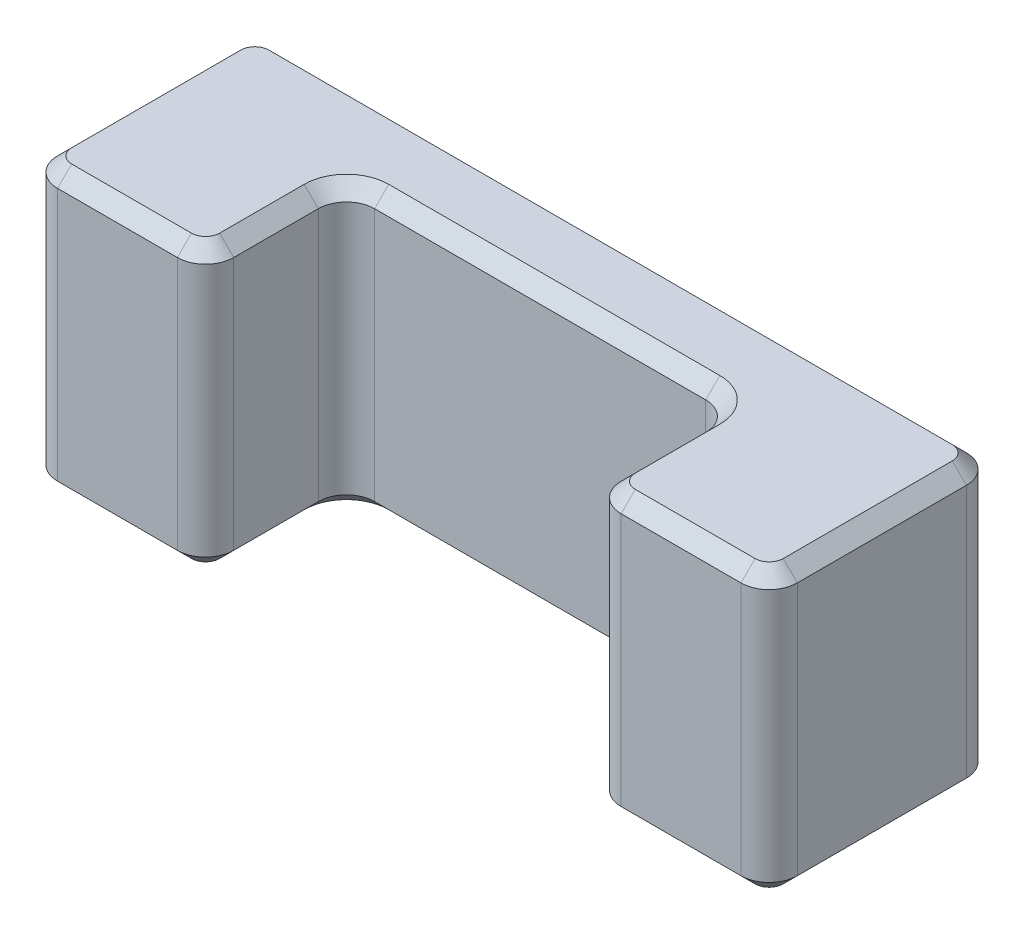
SolidWorks part; units mm, degrees
ref_plane "Front Plane" through (0, 0, 0) normal (0, 0, 1) x (1, 0, 0)
ref_plane "Top Plane" through (0, 0, 0) normal (0, 1, 0) x (1, 0, 0)
ref_plane "Right Plane" through (0, 0, 0) normal (1, 0, 0) x (0, 0, -1)
sketch "Sketch1" plane through (0, 0, 0) normal (0, 1, 0) x (1, 0, 0)
  line L0 (-10, 0) -> (10, 0) construction
  line L1 (-10, 0) -> (-10, 8.5068) construction
  line L2 (10, 0) -> (10, 9.6769) construction
  line L3 (0, 11.5732) -> (0, -7.2688) construction
  line L4 (-13.125, 0) -> (-13.125, -5)
  line L5 (-13.125, -5) -> (-6.875, -5)
  line L6 (-6.875, 0) -> (-6.875, -5)
  line L7 (-13.125, 0) -> (-13.125, 3)
  line L8 (-13.125, 3) -> (13.125, 3)
  line L9 (-6.875, 0) -> (6.875, 0)
  line L10 (13.125, 0) -> (13.125, 3)
  line L11 (13.125, 0) -> (13.125, -5)
  line L12 (13.125, -5) -> (6.875, -5)
  line L13 (6.875, 0) -> (6.875, -5)
  point P5 (-10, 0)
  point P9 (10, 0)
  point P14 (-10, -5)
  point P20 (0, 0)
  point P21 (0, 3)
  dimension "D1" = 20
  dimension "D2" = 6.25
  dimension "D3" = 5
  dimension "D4" = 3
extrude "Boss-Extrude1" add sketch "Sketch1" along normal blind 10
fillet "Fillet1" radius 1 8 edges at (13.125, 5, -3) (13.125, 5, 5) (6.875, 5, 5) (6.875, 5, 0) (-13.125, 5, -3) (-6.875, 5, 5) (-13.125, 5, 5) (-6.875, 5, 0)
chamfer "Chamfer1" distance 0.5 angle 45 32 edges at (12.8321, 10, 4.7071) (10, 10, 5) (7.1679, 10, 4.7071) (6.875, 10, 2.5) (6.5821, 10, 0.2929) (0, 10, 0) (-6.5821, 10, 0.2929) (-6.875, 10, 2.5) (-7.1679, 10, 4.7071) (-10, 10, 5) (-12.8321, 10, 4.7071) (-13.125, 10, 1) (-12.8321, 10, -2.7071) (0, 10, -3) (12.8321, 10, -2.7071) (13.125, 10, 1) (-12.8321, 0, -2.7071) (-13.125, 0, 1) (-12.8321, 0, 4.7071) (-10, 0, 5) (-7.1679, 0, 4.7071) (-6.875, 0, 2.5) (-6.5821, 0, 0.2929) (0, 0, 0) (6.5821, 0, 0.2929) (6.875, 0, 2.5) (7.1679, 0, 4.7071) (10, 0, 5) (12.8321, 0, 4.7071) (13.125, 0, 1) (12.8321, 0, -2.7071) (0, 0, -3)
